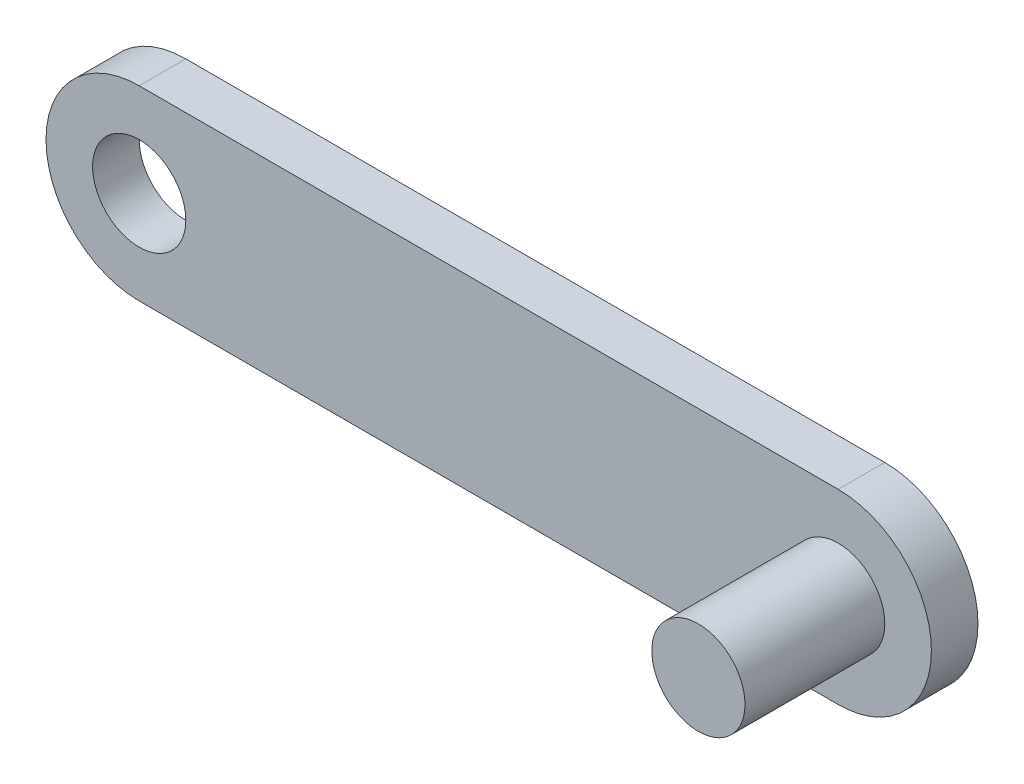
SolidWorks part; units mm, degrees
ref_plane "前视基准面" through (0, 0, 0) normal (0, 0, 1) x (1, 0, 0)
ref_plane "上视基准面" through (0, 0, 0) normal (0, 1, 0) x (1, 0, 0)
ref_plane "右视基准面" through (0, 0, 0) normal (1, 0, 0) x (0, 0, -1)
sketch "草图1" plane through (0, 0, 0) normal (0, 0, 1) x (1, 0, 0)
  line L0 (0, 2) -> (15, 2)
  line L1 (0, -2) -> (15, -2)
  line L2 (15, 2) -> (15, -2) construction
  circle A0 centre (0, 0) radius 1
  arc A1 (0, 2) -> (0, -2) centre (0, 0) ccw
  arc A3 (15, -2) -> (15, 2) centre (15, 0) ccw
  dimension "D1" = 2
  dimension "D2" = 4
  dimension "D3" = 15
  dimension "D4" = 15
extrude "凸台-拉伸1" add sketch "草图1" along normal blind 1
sketch "草图2" plane through (0, 0, 1) normal (0, 0, 1) x (1, 0, 0)
  circle A0 centre (15, 0) radius 1
  dimension "D1" = 2
extrude "凸台-拉伸2" add sketch "草图2" along normal blind 3
